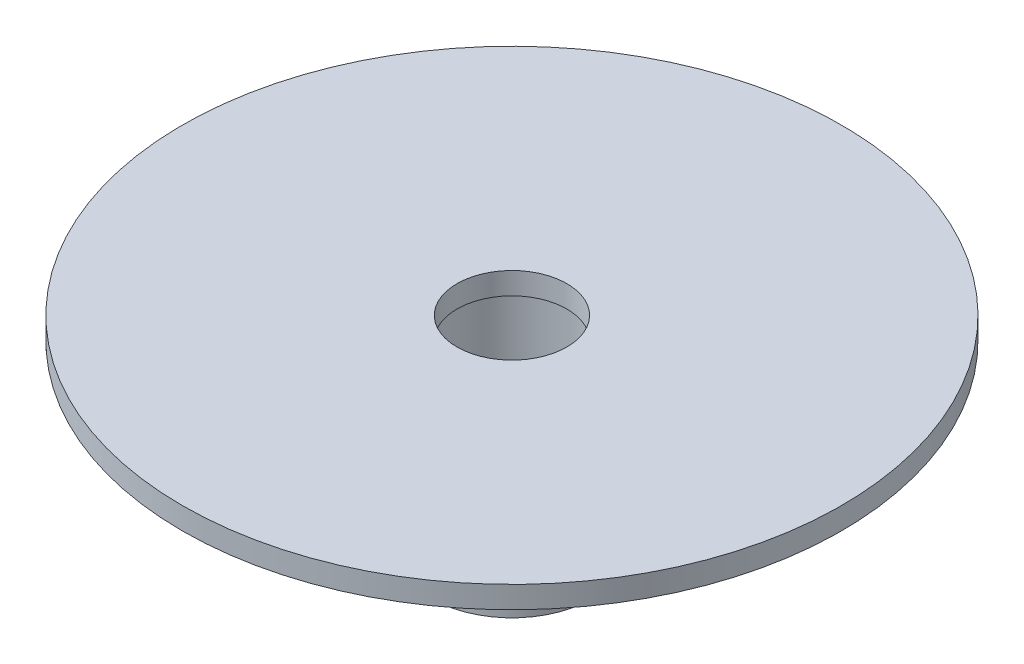
SolidWorks part; units mm, degrees
ref_plane "Front Plane" through (0, 0, 0) normal (0, 0, 1) x (1, 0, 0)
ref_plane "Top Plane" through (0, 0, 0) normal (0, 1, 0) x (1, 0, 0)
ref_plane "Right Plane" through (0, 0, 0) normal (1, 0, 0) x (0, 0, -1)
sketch "Sketch1" plane through (0, 0, 0) normal (0, 1, 0) x (1, 0, 0)
  circle A0 centre (0, 0) radius 45
  circle A1 centre (0, 0) radius 7.5
  dimension "D1" = 90
  dimension "D2" = 15
extrude "Boss-Extrude1" add sketch "Sketch1" along normal blind 3 contours A1 | A0
sketch "Sketch2" plane through (0, 0, 0) normal (0, -1, 0) x (1, 0, 0)
  circle A0 centre (0, 0) radius 11
  circle A1 centre (0, 0) radius 9
  dimension "D1" = 22
  dimension "D2" = 18
extrude "Boss-Extrude2" add sketch "Sketch2" along normal blind 25 contours A0 | A1
